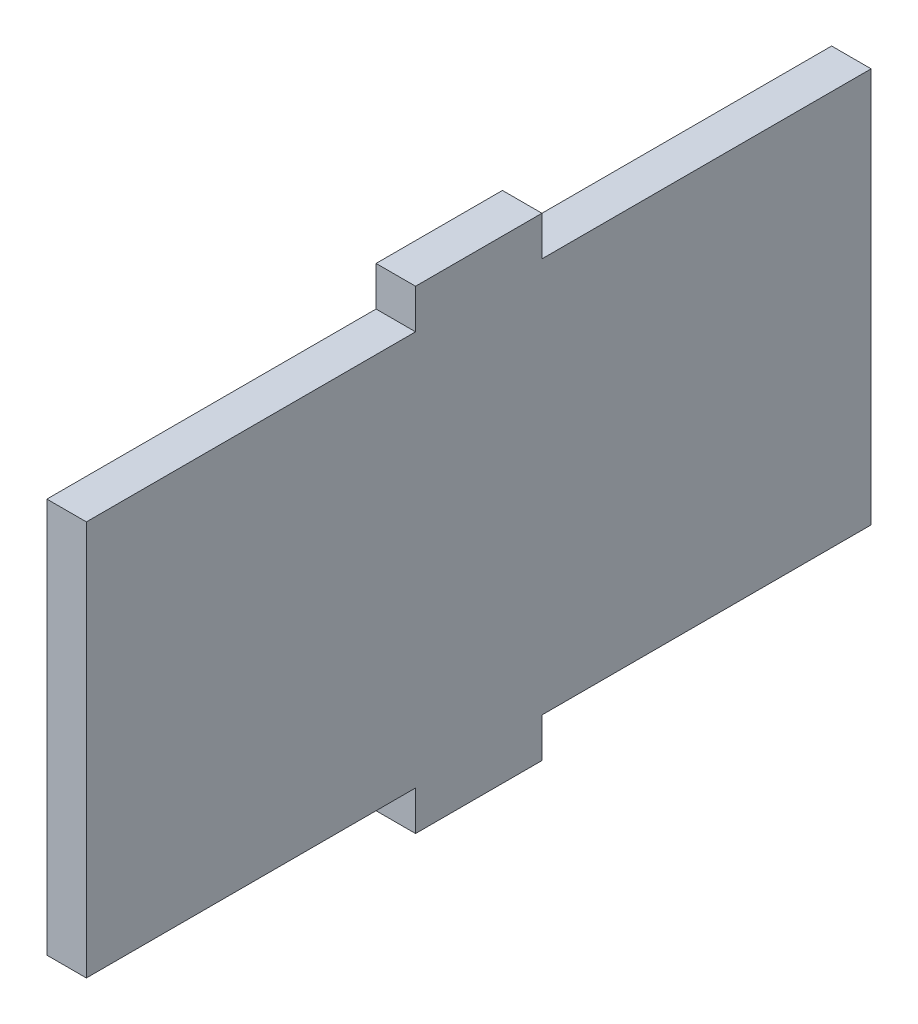
SolidWorks part; units mm, degrees
material "3mm Birch Ply Wood"
ref_plane "Front Plane" through (0, 0, 0) normal (0, 0, 1) x (1, 0, 0)
ref_plane "Top Plane" through (0, 0, 0) normal (0, 1, 0) x (1, 0, 0)
ref_plane "Right Plane" through (0, 0, 0) normal (1, 0, 0) x (0, 0, -1)
sketch "Sketch1" plane through (0, 0, 0) normal (1, 0, 0) x (0, 0, -1)
  line L0 (4.8, 41) -> (4.8, 38)
  line L1 (4.8, 5) -> (-4.8, 5)
  line L2 (-4.8, 5) -> (-4.8, 8)
  line L3 (-4.8, 8) -> (-29.8, 8)
  line L4 (-29.8, 8) -> (-29.8, 38)
  line L5 (29.8, 8) -> (29.8, 38)
  line L6 (4.8, 8) -> (29.8, 8)
  line L7 (4.8, 5) -> (4.8, 8)
  line L8 (29.8, 23) -> (-29.8, 23) construction
  line L19 (4.8, 38) -> (29.8, 38)
  line L20 (-4.8, 38) -> (-29.8, 38)
  line L21 (-4.8, 41) -> (-4.8, 38)
  line L22 (4.8, 41) -> (-4.8, 41)
  point P11 (0, 23)
  point P13 (0, 23)
extrude "Boss-Extrude1" add sketch "Sketch1" along normal blind 3
